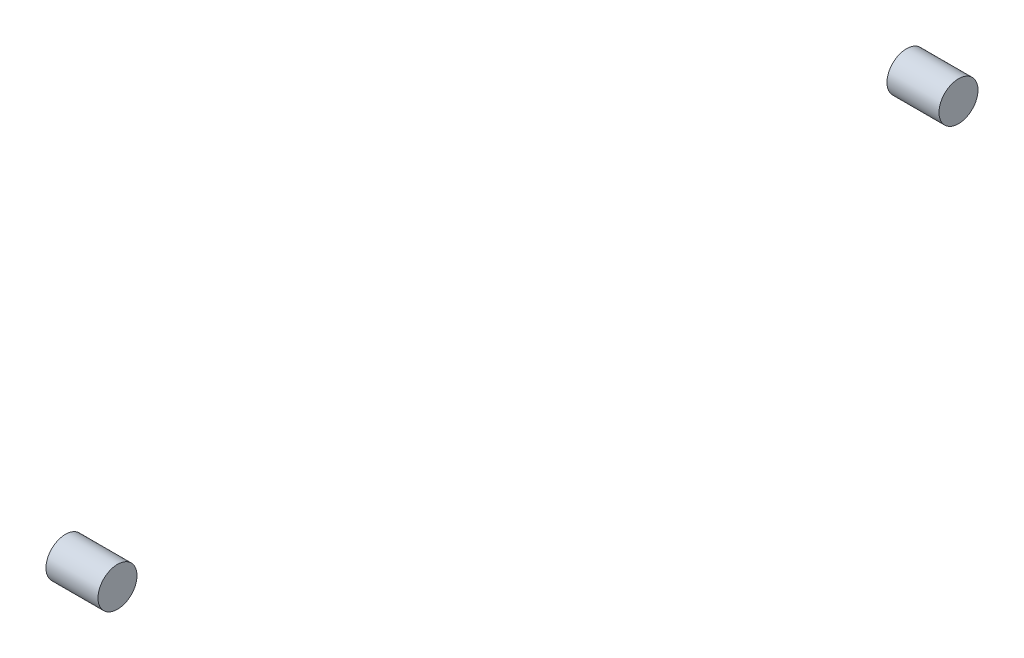
SolidWorks part; units mm, degrees
ref_plane "Front Plane" through (0, 0, 0) normal (0, 0, 1) x (1, 0, 0)
ref_plane "Top Plane" through (0, 0, 0) normal (0, 1, 0) x (1, 0, 0)
ref_plane "Right Plane" through (0, 0, 0) normal (1, 0, 0) x (0, 0, -1)
sketch "Sketch1" plane through (0, 0, 0) normal (1, 0, 0) x (0, 0, -1)
  circle A0 centre (1940, -80) radius 90
extrude "Boss-Extrude1" add sketch "Sketch1" along normal blind 240 from offset 1170
sketch "Sketch2" plane through (0, 0, 0) normal (1, 0, 0) x (0, 0, -1)
  circle A0 centre (-1940, -80) radius 90
extrude "Boss-Extrude2" add sketch "Sketch2" along normal blind 240 from offset 1170
